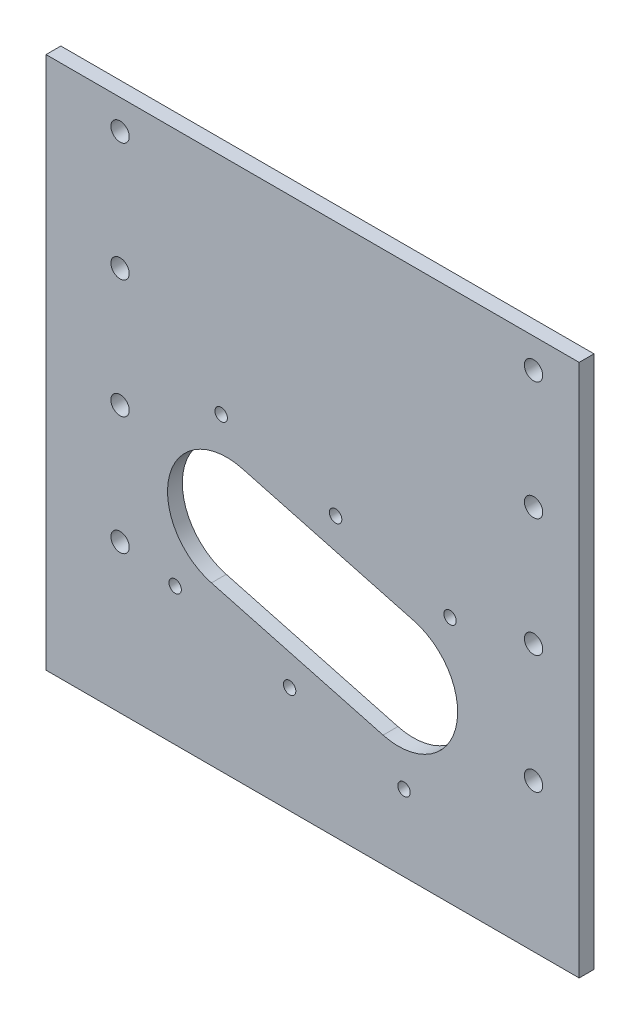
SolidWorks part; units mm, degrees
material "Thornel Mat VMA"
ref_plane "Front Plane" through (0, 0, 0) normal (0, 0, 1) x (1, 0, 0)
ref_plane "Top Plane" through (0, 0, 0) normal (0, 1, 0) x (1, 0, 0)
ref_plane "Right Plane" through (0, 0, 0) normal (1, 0, 0) x (0, 0, -1)
sketch "Sketch1" plane through (0, 0, 0) normal (0, 0, 1) x (1, 0, 0)
  line L1 (-90, -90) -> (90, -90)
  line L2 (-90, -90) -> (-90, 90)
  line L3 (-90, 90) -> (90, 90)
  line L4 (90, -90) -> (90, 90)
  line L5 (-90, -90) -> (90, 90) construction
  line L6 (-90, 90) -> (90, -90) construction
  point P0 (0, 0)
  dimension "D1" = 180
  dimension "D2" = 180
extrude "Boss-Extrude1" add sketch "Sketch1" along normal blind 5
sketch "Sketch2" plane through (0, 0, 0) normal (0, 0, -1) x (-1, 0, 0)
  line L0 (-90, 40) -> (-9.8, 90)
  line L1 (-90, -90) -> (-90, 90) construction
  line L2 (-90, 90) -> (90, 90) construction
  line L3 (-9.8, 90) -> (-90, 90)
  line L4 (-90, 90) -> (-90, 40)
  dimension "D1" = 50
  dimension "D2" = 80.2
sketch "Sketch3" plane through (0, 0, 0) normal (0, 0, -1) x (-1, 0, 0)
  line L0 (-28.9778, -32.7646) -> (28.9778, -17.2354) construction
  line L1 (-34.1542, -13.4461) -> (23.8014, 2.0831)
  line L2 (-23.8014, -52.0831) -> (34.1542, -36.5539)
  line L3 (90, -90) -> (-90, -90) construction
  arc A0 (-34.1542, -13.4461) -> (-23.8014, -52.0831) centre (-28.9778, -32.7646) ccw
  arc A1 (34.1542, -36.5539) -> (23.8014, 2.0831) centre (28.9778, -17.2354) ccw
  point P2 (0, -25)
  dimension "D4" = 20
  dimension "D1" = 15
  dimension "D2" = 25
  dimension "D3" = 60
extrude "Cut-Extrude1" cut sketch "Sketch3" against normal through all
sketch "Sketch4" plane through (0, 0, 5) normal (0, 0, 1) x (1, 0, 0)
  line L0 (-65, 90) -> (-65, 80) construction
  line L1 (90, 90) -> (-90, 90) construction
  line L2 (-90, 90) -> (-90, -90) construction
  circle A0 centre (-65, 80) radius 3.1
  circle A1 centre (-65, 40) radius 3.1
  circle A2 centre (-65, 0) radius 3.1
  circle A3 centre (-65, -40) radius 3.1
  dimension "D1" = 6.2
  dimension "D5" = 40
  dimension "D2" = 25
  dimension "D3" = 10
  dimension "D4" = 4
extrude "Cut-Extrude2" cut sketch "Sketch4" against normal through all
sketch "Sketch5" plane through (0, 0, 0) normal (0, 0, -1) x (-1, 0, 0)
  line L0 (-90, -90) -> (-90, 90) construction
  line L1 (-74.6004, 80) -> (-74.6004, 90) construction
  line L2 (-90, 90) -> (90, 90) construction
  circle A0 centre (-74.6004, 80) radius 3.1
  circle A1 centre (-74.6004, 40) radius 3.1
  circle A2 centre (-74.6004, 0) radius 3.1
  circle A3 centre (-74.6004, -40) radius 3.1
  dimension "D1" = 6.2
  dimension "D2" = 15.3996
  dimension "D3" = 10
  dimension "D5" = 40
  dimension "D4" = 4
extrude "Cut-Extrude3" cut sketch "Sketch5" against normal through all
sketch "Sketch6" plane through (0, 0, 0) normal (0, 0, -1) x (-1, 0, 0)
  line L0 (-48.2963, -37.941) -> (48.2963, -12.059) construction
  line L1 (0, -25) -> (-7.7646, 3.9778) construction
  arc A0 (-34.1542, -13.4461) -> (-23.8014, -52.0831) centre (-28.9778, -32.7646) ccw construction
  arc A1 (34.1542, -36.5539) -> (23.8014, 2.0831) centre (28.9778, -17.2354) ccw construction
  circle A2 centre (-7.7646, 3.9778) radius 2.1
  circle A3 centre (7.7646, -53.9778) radius 2.1
  circle A4 centre (46.4016, -43.625) radius 2.1
  circle A5 centre (30.8725, 14.3305) radius 2.1
  circle A6 centre (-30.8725, -64.3305) radius 2.1
  circle A7 centre (-46.4016, -6.375) radius 2.1
  dimension "D2" = 4.2
  dimension "D1" = 30
  dimension "D4" = 40
  dimension "D3" = 2
extrude "Cut-Extrude4" cut sketch "Sketch6" against normal through all
